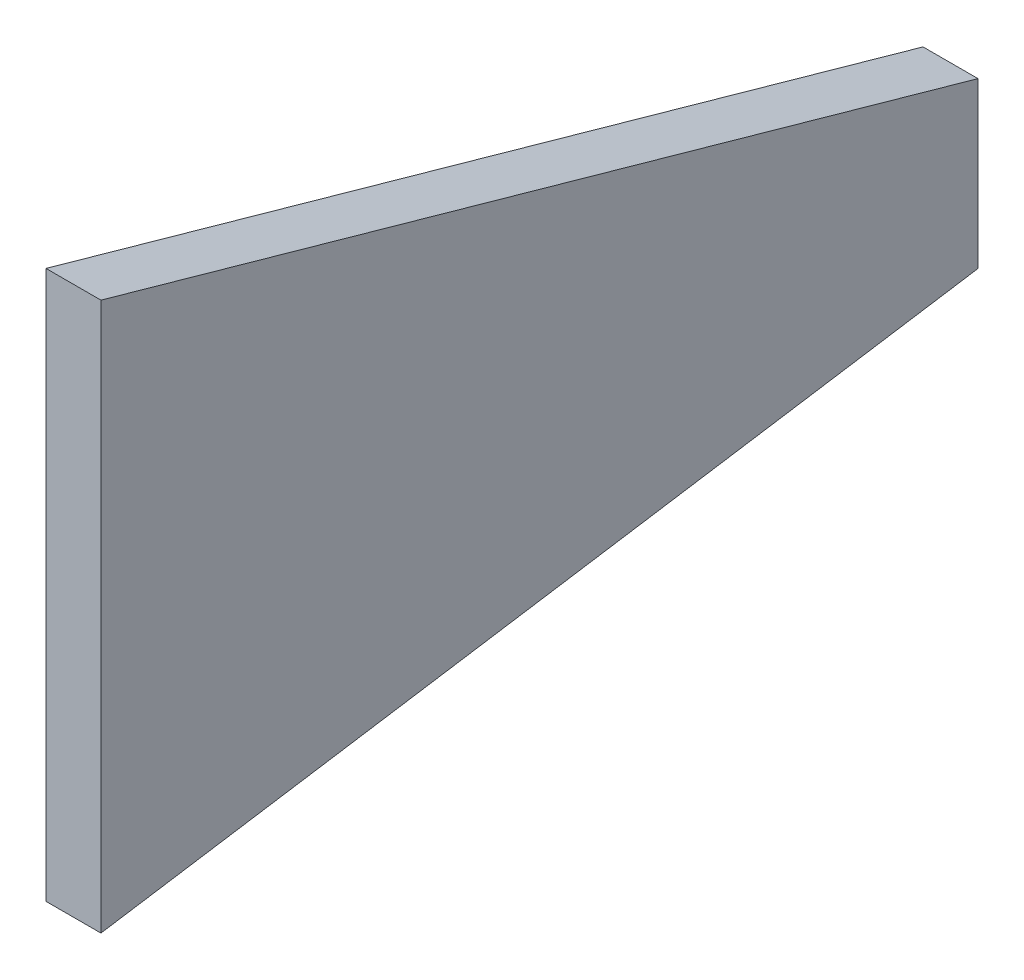
SolidWorks part; units mm, degrees
ref_plane "Ön Düzlem" through (0, 0, 0) normal (0, 0, 1) x (1, 0, 0)
ref_plane "Üst Düzlem" through (0, 0, 0) normal (0, 1, 0) x (1, 0, 0)
ref_plane "Sağ Düzlem" through (0, 0, 0) normal (1, 0, 0) x (0, 0, -1)
sketch "Sketch1" plane through (0, 0, 0) normal (0, 1, 0) x (1, 0, 0)
  line L4 (-10, -150) -> (0, 0)
  line L5 (0, 0) -> (-10.0222, 0)
  line L6 (-10.0222, 0) -> (-20.0222, -150)
  line L7 (-20.0222, -150) -> (-10, -150)
extrude "Boss-Extrude1" add sketch "Sketch1" along normal blind 100
sketch "Sketch3" plane through (0, 0, 0) normal (1, 0, 0) x (0, 0, -1)
  line L0 (-150, 100) -> (0, 100)
  line L1 (0, 100) -> (0, 65)
  line L2 (0, 65) -> (-150, 100)
  line L3 (0, 50) -> (-150, 50) construction
  line L4 (0, 35) -> (-150, 0)
  line L5 (0, 0) -> (0, 35)
  line L6 (-150, 0) -> (0, 0)
  line L7 (-150, 100) -> (0, 100)
  line L8 (0, 100) -> (0, 65)
  line L9 (0, 65) -> (-150, 100)
  line L10 (0, 35) -> (-150, 0)
  line L11 (0, 0) -> (0, 35)
  line L12 (-150, 0) -> (0, 0)
  line L13 (-150, 100) -> (-150, 0) construction
  dimension "D1" = 150
  dimension "D2" = 150
extrude "Cut-Extrude2" cut sketch "Sketch3" against normal blind 65 contours L2 L1 L0 | L4 L6 L5
